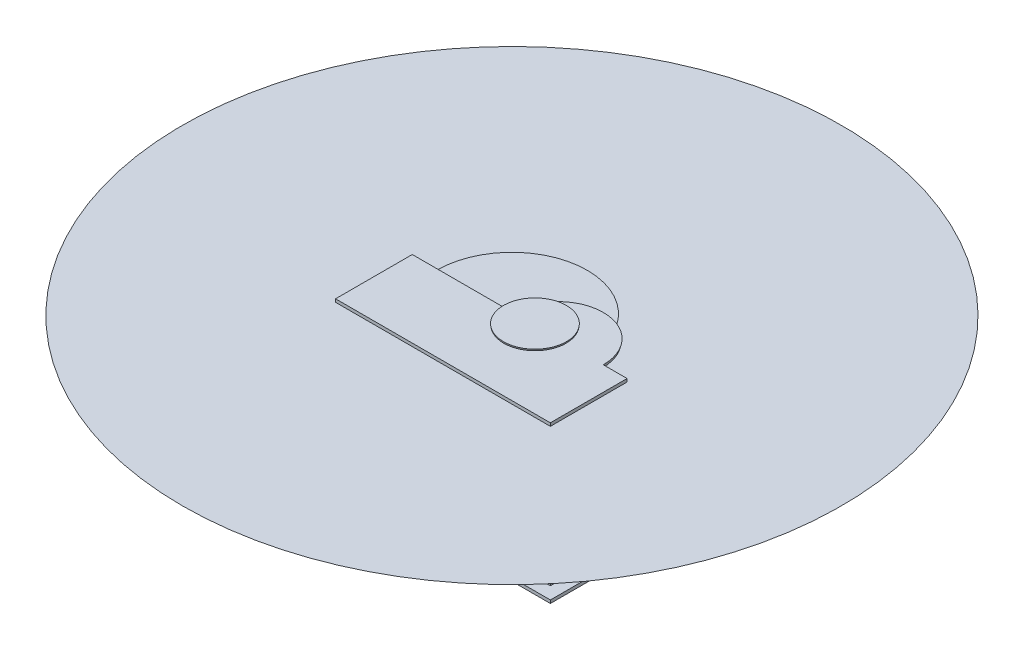
SolidWorks part; units mm, degrees
ref_plane "Front Plane" through (0, 0, 0) normal (0, 0, 1) x (1, 0, 0)
ref_plane "Top Plane" through (0, 0, 0) normal (0, 1, 0) x (1, 0, 0)
ref_plane "Right Plane" through (0, 0, 0) normal (1, 0, 0) x (0, 0, -1)
sketch "Sketch1" plane through (0, 0, 0) normal (0, 1, 0) x (1, 0, 0)
  circle A0 centre (0, 0) radius 0.25
  dimension "D1" = 0.5
extrude "Boss-Extrude1" add sketch "Sketch1" along normal blind 10.1 draft 15 draft outward yes
sketch "Sketch2" plane through (0, 0, 0) normal (0, -1, 0) x (1, 0, 0)
  circle A0 centre (-3, 0) radius 0.25
  dimension "D1" = 0.5
  dimension "D2" = 3
extrude "Boss-Extrude2" add sketch "Sketch2" against normal blind 10 draft 25 separate body draft outward yes
sketch "Sketch3" plane through (0, 0, 0) normal (0, 0, 1) x (1, 0, 0)
  line L0 (-9.4953, 0) -> (4.5047, 0)
  line L1 (-9.4953, 1) -> (4.5047, 1)
  line L2 (-9.4953, 2) -> (4.5047, 2)
  line L3 (-9.4953, 3) -> (4.5047, 3)
  line L4 (-9.4953, 4) -> (4.5047, 4)
  line L5 (-9.4953, 5) -> (4.5047, 5)
  line L6 (-9.4953, 6) -> (4.5047, 6)
  line L7 (-9.4953, 7) -> (4.5047, 7)
  line L8 (-9.4953, 8) -> (4.5047, 8)
  line L9 (-9.4953, 9) -> (4.5047, 9)
  line L10 (-9.4953, 10) -> (4.5047, 10)
  dimension "D1" = 11
extrude "Extrude-Thin1" add sketch "Sketch3" along normal blind 5 thin
sketch "Sketch4" plane through (0, 0, 0) normal (0, 1, 0) x (1, 0, 0)
  line L1 (-4.05, -1.05) -> (-1.95, -1.05)
  line L2 (-4.05, -1.05) -> (-4.05, 1.05)
  line L3 (-4.05, 1.05) -> (-1.95, 1.05)
  line L4 (-1.95, -1.05) -> (-1.95, 1.05)
  line L5 (-4.05, -1.05) -> (-1.95, 1.05) construction
  line L6 (-4.05, 1.05) -> (-1.95, -1.05) construction
  point P0 (-3, 0)
  dimension "D1" = 2.1
  dimension "D2" = 2.1
extrude "Boss-Extrude3" add sketch "Sketch4" against normal blind 0.7
sketch "Sketch5" plane through (0, 0, 0) normal (0, -1, 0) x (1, 0, 0)
  line L1 (-1, 1.9) -> (1, 1.9)
  line L2 (-1, 1.9) -> (-1, -1.9)
  line L3 (-1, -1.9) -> (1, -1.9)
  line L4 (1, 1.9) -> (1, -1.9)
  line L5 (-1, 1.9) -> (1, -1.9) construction
  line L6 (-1, -1.9) -> (1, 1.9) construction
  point P0 (0, 0)
  dimension "D1" = 2
  dimension "D2" = 3.8
extrude "Boss-Extrude4" add sketch "Sketch5" along normal blind 2.1
sketch "Sketch7" plane through (0, 0, 0) normal (0, 1, 0) x (1, 0, 0)
  line L0 (-1.95, 0) -> (-1, 0) construction
  circle A0 centre (-3, 0) radius 0.25
  dimension "D1" = 0.5
  dimension "D2" = 3
extrude "Boss-Extrude5" add sketch "Sketch7" along normal blind 9.9 draft 65 draft outward yes
sketch "Sketch8" plane through (0, 0, 0) normal (0, -1, 0) x (1, 0, 0)
  line L1 (-3.4, 0.8) -> (-2.6, 0.8)
  line L2 (-3.4, 0.8) -> (-3.4, -0.8)
  line L3 (-3.4, -0.8) -> (-2.6, -0.8)
  line L4 (-2.6, 0.8) -> (-2.6, -0.8)
  line L5 (-3.4, 0.8) -> (-2.6, -0.8) construction
  line L6 (-3.4, -0.8) -> (-2.6, 0.8) construction
  point P0 (-3, 0)
  dimension "D1" = 1.6
  dimension "D2" = 0.8
extrude "Boss-Extrude6" add sketch "Sketch8" along normal blind 0.8
sketch "Sketch9" plane through (0, 0, 0) normal (0, 1, 0) x (1, 0, 0)
  circle A0 centre (-1.5, 0) radius 0.25
  point P2 (0, 0)
  dimension "D1" = 0.5
  dimension "D2" = 1.5
extrude "Boss-Extrude7" add sketch "Sketch9" along normal blind 10.2 draft 10 draft outward yes
